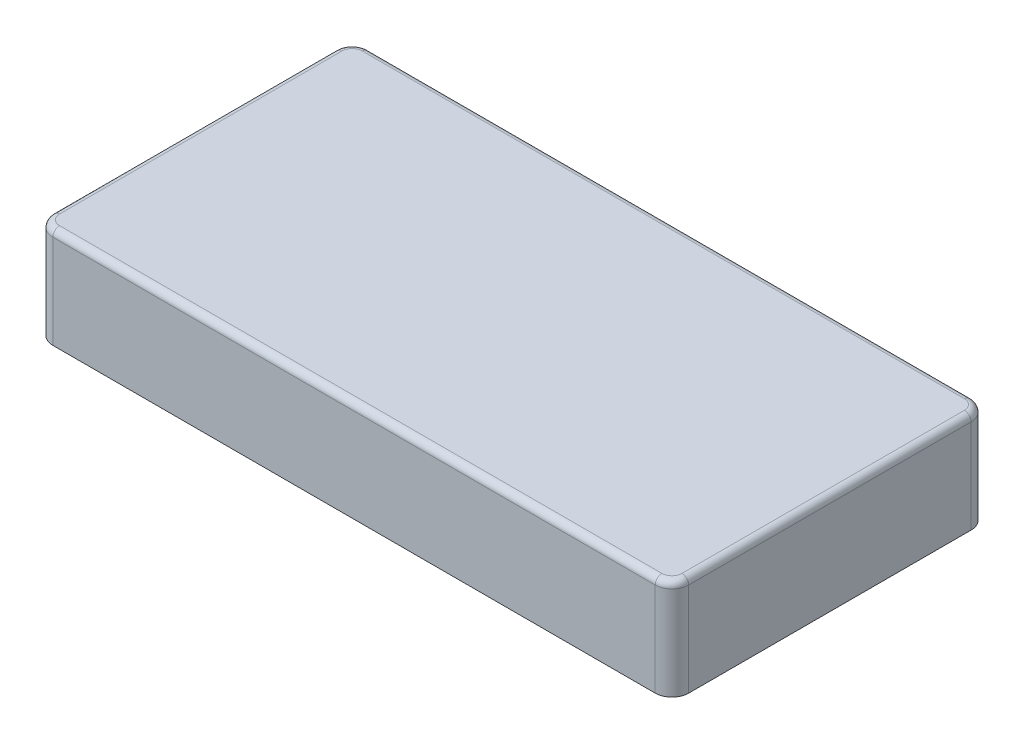
SolidWorks part; units mm, degrees
ref_plane "Спереди" through (0, 0, 0) normal (0, 0, 1) x (1, 0, 0)
ref_plane "Сверху" through (0, 0, 0) normal (0, 1, 0) x (1, 0, 0)
ref_plane "Справа" through (0, 0, 0) normal (1, 0, 0) x (0, 0, -1)
sketch "Эскиз1" plane through (0, 0, 0) normal (0, 1, 0) x (1, 0, 0)
  line L1 (-9, 4.72) -> (9, 4.72)
  line L2 (-9.5, 4.22) -> (-9.5, -4.22)
  line L3 (-9, -4.72) -> (9, -4.72)
  line L4 (9.5, 4.22) -> (9.5, -4.22)
  line L5 (-9.5, 4.72) -> (9.5, -4.72) construction
  line L6 (-9.5, -4.72) -> (9.5, 4.72) construction
  arc A0 (9, 4.72) -> (9.5, 4.22) centre (9, 4.22) cw
  arc A1 (9.5, -4.22) -> (9, -4.72) centre (9, -4.22) cw
  arc A2 (-9, -4.72) -> (-9.5, -4.22) centre (-9, -4.22) cw
  arc A3 (-9, 4.72) -> (-9.5, 4.22) centre (-9, 4.22) ccw
  point P0 (0, 0)
  dimension "D3" = 0.5
  dimension "D1" = 19
  dimension "D2" = 9.44
extrude "Бобышка-Вытянуть1" add sketch "Эскиз1" along normal blind 3
fillet "Скругление1" radius 0.2 8 edges at (9.3536, 3, 4.5736) (9.3536, 3, -4.5736) (9.5, 3, 0) (-9.3536, 3, 4.5736) (-9.3536, 3, -4.5736) (-9.5, 3, 0) (0, 3, -4.72) (0, 3, 4.72)
